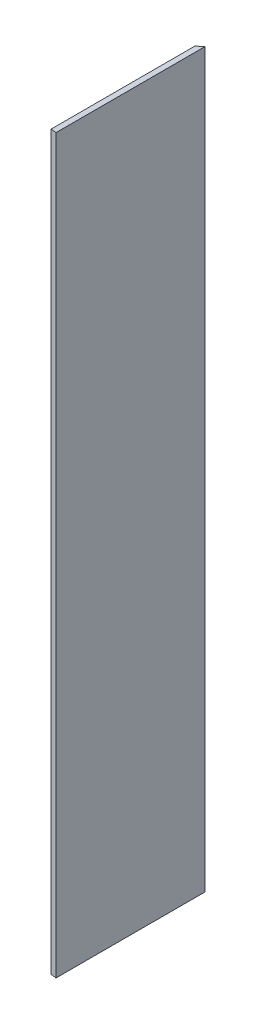
SolidWorks part; units mm, degrees
ref_plane "Спереди" through (0, 0, 0) normal (0, 0, 1) x (1, 0, 0)
ref_plane "Сверху" through (0, 0, 0) normal (0, 1, 0) x (1, 0, 0)
ref_plane "Справа" through (0, 0, 0) normal (1, 0, 0) x (0, 0, -1)
sketch "Эскиз1" plane through (0, 0, 0) normal (0, 1, 0) x (1, 0, 0)
  line L0 (1.0264, -2.6326) -> (1.0264, -107.3249)
  line L1 (1.0264, -107.3249) -> (5.0264, -107.8388)
  line L2 (5.0264, -107.8388) -> (5.0264, 0.4912)
  line L3 (5.0264, 0.4912) -> (1.0264, -2.6326)
  line L4 (0.2179, -107.1085) -> (4.8056, -108.3365) construction
  dimension "D1" = 4
extrude "Вытянуть1" add sketch "Эскиз1" along normal blind 533
